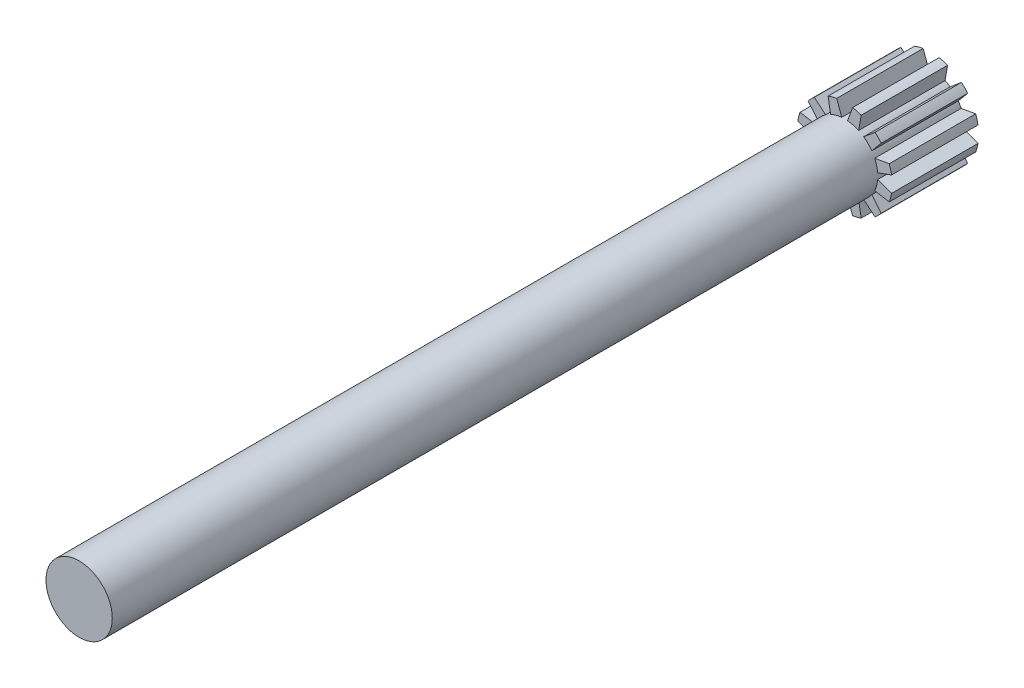
SolidWorks part; units mm, degrees
ref_plane "Front Plane" through (0, 0, 0) normal (0, 0, 1) x (1, 0, 0)
ref_plane "Top Plane" through (0, 0, 0) normal (0, 1, 0) x (1, 0, 0)
ref_plane "Right Plane" through (0, 0, 0) normal (1, 0, 0) x (0, 0, -1)
sketch "Sketch1" plane through (0, 0, 0) normal (0, 0, 1) x (1, 0, 0)
  circle A0 centre (0, 0) radius 57.5
  dimension "D1" = 115
extrude "Boss-Extrude1" add sketch "Sketch1" along normal blind 1328
sketch "Sketch3" plane through (0, 0, 0) normal (0, 0, -1) x (-1, 0, 0)
  circle A1 centre (0, 0) radius 82.5
  dimension "D1" = 165
extrude "Boss-Extrude2" add sketch "Sketch3" along normal blind 150
sketch "Sketch5" plane through (0, 0, -150) normal (0, 0, -1) x (-1, 0, 0)
  line L0 (0, 0) -> (0, 101.6016) construction
  line L1 (0, 43.4062) -> (-13.8056, 81.3367) construction
  line L2 (0, 43.4062) -> (13.8056, 81.3367) construction
  line L3 (-13.8056, 81.3367) -> (-5.0489, 57.2779)
  line L4 (13.8056, 81.3367) -> (5.0489, 57.2779)
  arc A0 (-5.0489, 57.2779) -> (5.0489, 57.2779) centre (0, 0) cw
  circle A1 centre (0, 0) radius 82.5 construction
  arc A2 (-13.8056, 81.3367) -> (13.8056, 81.3367) centre (0, 0) cw
  point P5 (0, 57.5)
  dimension "D1" = 57.5
  dimension "D2" = 20
  dimension "D3" = 20
extrude "Cut-Extrude1" cut sketch "Sketch5" against normal blind 150
pattern_circular "CirPattern1" count 12 over 360 about axis through (0, 0, 0) along (0, 0, 1) of "Cut-Extrude1"
